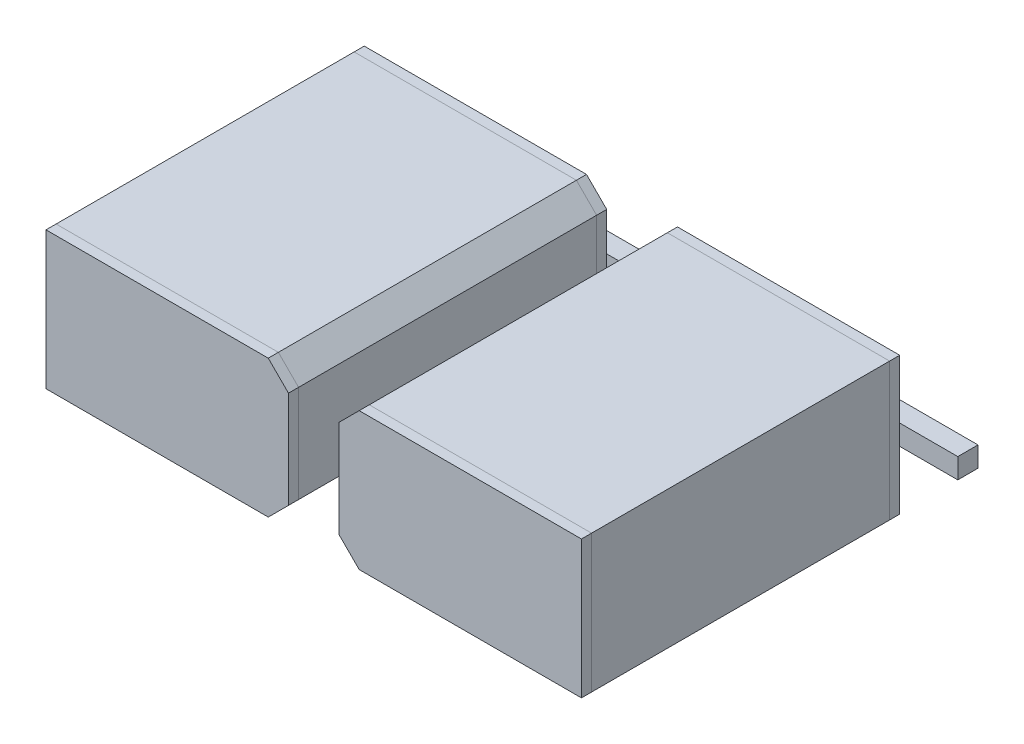
SolidWorks part; units mm, degrees
ref_plane "Alzado" through (0, 0, 0) normal (0, 0, 1) x (1, 0, 0)
ref_plane "Planta" through (0, 0, 0) normal (0, 1, 0) x (1, 0, 0)
ref_plane "Vista lateral" through (0, 0, 0) normal (1, 0, 0) x (0, 0, -1)
sketch "Croquis1" plane through (0, 0, 0) normal (0, 0, 1) x (1, 0, 0)
  line L1 (0, 0) -> (400, 0) construction
  line L2 (0, 0) -> (0, 150) construction
  line L3 (0, 150) -> (400, 150) construction
  line L4 (400, 0) -> (400, 150) construction
  line L5 (31.75, 31.75) -> (184.125, 31.75)
  line L6 (31.75, 31.75) -> (31.75, 118.25)
  line L7 (31.75, 118.25) -> (184.125, 118.25)
  line L8 (184.125, 31.75) -> (184.125, 118.25)
  line L9 (215.875, 118.25) -> (368.25, 118.25)
  line L10 (215.875, 118.25) -> (215.875, 31.75)
  line L11 (215.875, 31.75) -> (368.25, 31.75)
  line L12 (368.25, 118.25) -> (368.25, 31.75)
  point P13 (0, 0)
  point P14 (0, 0)
  dimension "D1" = 150
  dimension "D2" = 400
  dimension "D3" = 31.75
  dimension "D4" = 31.75
  dimension "D5" = 31.75
  dimension "D6" = 31.75
  dimension "D7" = 31.75
  dimension "D8" = 31.75
extrude "Saliente-Extruir1" add sketch "Croquis1" along normal blind 6.35
chamfer "Chaflán1" distance 12.7 angle 45 2 edges at (184.125, 31.75, 3.175) (184.125, 118.25, 3.175)
chamfer "Chaflán2" distance 12.7 angle 45 2 edges at (215.875, 31.75, 3.175) (215.875, 118.25, 3.175)
sketch "Croquis2" plane through (0, 0, 6.35) normal (0, 0, 1) x (1, 0, 0)
  line L0 (215.875, 105.55) -> (215.875, 44.45) construction
  line L1 (215.875, 44.45) -> (228.575, 31.75) construction
  line L2 (228.575, 31.75) -> (368.25, 31.75) construction
  line L3 (368.25, 31.75) -> (368.25, 118.25) construction
  line L4 (368.25, 118.25) -> (228.575, 118.25) construction
  line L5 (228.575, 118.25) -> (215.875, 105.55) construction
  line L6 (31.75, 31.75) -> (171.425, 31.75) construction
  line L7 (171.425, 31.75) -> (184.125, 44.45) construction
  line L8 (184.125, 44.45) -> (184.125, 105.55) construction
  line L9 (184.125, 105.55) -> (171.425, 118.25) construction
  line L10 (171.425, 118.25) -> (31.75, 118.25) construction
  line L11 (31.75, 118.25) -> (31.75, 31.75) construction
  line L12 (215.875, 105.55) -> (215.875, 44.45)
  line L13 (215.875, 44.45) -> (228.575, 31.75)
  line L14 (228.575, 31.75) -> (368.25, 31.75)
  line L15 (368.25, 31.75) -> (368.25, 118.25)
  line L16 (368.25, 118.25) -> (228.575, 118.25)
  line L17 (228.575, 118.25) -> (215.875, 105.55)
  line L18 (31.75, 31.75) -> (171.425, 31.75)
  line L19 (171.425, 31.75) -> (184.125, 44.45)
  line L20 (184.125, 44.45) -> (184.125, 105.55)
  line L21 (184.125, 105.55) -> (171.425, 118.25)
  line L22 (171.425, 118.25) -> (31.75, 118.25)
  line L23 (31.75, 118.25) -> (31.75, 31.75)
  line L24 (168.7947, 111.9) -> (38.1, 111.9)
  line L25 (38.1, 111.9) -> (38.1, 38.1)
  line L26 (38.1, 38.1) -> (168.7947, 38.1)
  line L27 (168.7947, 38.1) -> (177.775, 47.0803)
  line L28 (177.775, 47.0803) -> (177.775, 102.9197)
  line L29 (177.775, 102.9197) -> (168.7947, 111.9)
  line L42 (222.225, 102.9197) -> (222.225, 47.0803)
  line L43 (222.225, 47.0803) -> (231.2053, 38.1)
  line L44 (231.2053, 38.1) -> (361.9, 38.1)
  line L45 (361.9, 38.1) -> (361.9, 111.9)
  line L46 (361.9, 111.9) -> (231.2053, 111.9)
  line L47 (231.2053, 111.9) -> (222.225, 102.9197)
  line L48 (222.225, 102.9197) -> (222.225, 47.0803)
  line L49 (222.225, 47.0803) -> (231.2053, 38.1)
  line L50 (231.2053, 38.1) -> (361.9, 38.1)
  line L51 (361.9, 38.1) -> (361.9, 111.9)
  line L52 (361.9, 111.9) -> (231.2053, 111.9)
  line L53 (231.2053, 111.9) -> (222.225, 102.9197)
  dimension "D1" = 6.35
  dimension "D2" = 6.35
extrude "Saliente-Extruir2" add sketch "Croquis2" along normal blind 187.3 separate body
sketch "Croquis3" plane through (0, 0, 193.65) normal (0, 0, 1) x (1, 0, 0)
  line L0 (368.25, 31.75) -> (228.575, 31.75) construction
  line L1 (228.575, 31.75) -> (215.875, 44.45) construction
  line L2 (215.875, 44.45) -> (215.875, 105.55) construction
  line L3 (215.875, 105.55) -> (228.575, 118.25) construction
  line L4 (228.575, 118.25) -> (368.25, 118.25) construction
  line L5 (368.25, 118.25) -> (368.25, 31.75) construction
  line L6 (184.125, 105.55) -> (184.125, 44.45) construction
  line L7 (184.125, 44.45) -> (171.425, 31.75) construction
  line L8 (171.425, 31.75) -> (31.75, 31.75) construction
  line L9 (31.75, 31.75) -> (31.75, 118.25) construction
  line L10 (31.75, 118.25) -> (171.425, 118.25) construction
  line L11 (171.425, 118.25) -> (184.125, 105.55) construction
  line L12 (368.25, 31.75) -> (228.575, 31.75)
  line L13 (228.575, 31.75) -> (215.875, 44.45)
  line L14 (215.875, 44.45) -> (215.875, 105.55)
  line L15 (215.875, 105.55) -> (228.575, 118.25)
  line L16 (228.575, 118.25) -> (368.25, 118.25)
  line L17 (368.25, 118.25) -> (368.25, 31.75)
  line L18 (184.125, 105.55) -> (184.125, 44.45)
  line L19 (184.125, 44.45) -> (171.425, 31.75)
  line L20 (171.425, 31.75) -> (31.75, 31.75)
  line L21 (31.75, 31.75) -> (31.75, 118.25)
  line L22 (31.75, 118.25) -> (171.425, 118.25)
  line L23 (171.425, 118.25) -> (184.125, 105.55)
extrude "Saliente-Extruir3" add sketch "Croquis3" along normal blind 6.35
sketch "Croquis4" plane through (0, 0, 0) normal (0, 0, -1) x (-1, 0, 0)
  line L0 (-31.75, 75) -> (-368.25, 75) construction
  line L1 (-31.75, 118.25) -> (-31.75, 31.75) construction
  line L2 (-368.25, 31.75) -> (-368.25, 118.25) construction
  line L4 (4.75, 68.65) -> (-404.75, 68.65)
  line L5 (4.75, 68.65) -> (4.75, 81.35)
  line L6 (4.75, 81.35) -> (-404.75, 81.35)
  line L7 (-404.75, 68.65) -> (-404.75, 81.35)
  line L8 (4.75, 68.65) -> (-404.75, 81.35) construction
  line L9 (4.75, 81.35) -> (-404.75, 68.65) construction
  point P6 (-200, 75)
  dimension "D1" = 12.7
  dimension "D2" = 409.5
extrude "Saliente-Extruir4" add sketch "Croquis4" along normal blind 12.7 separate body
